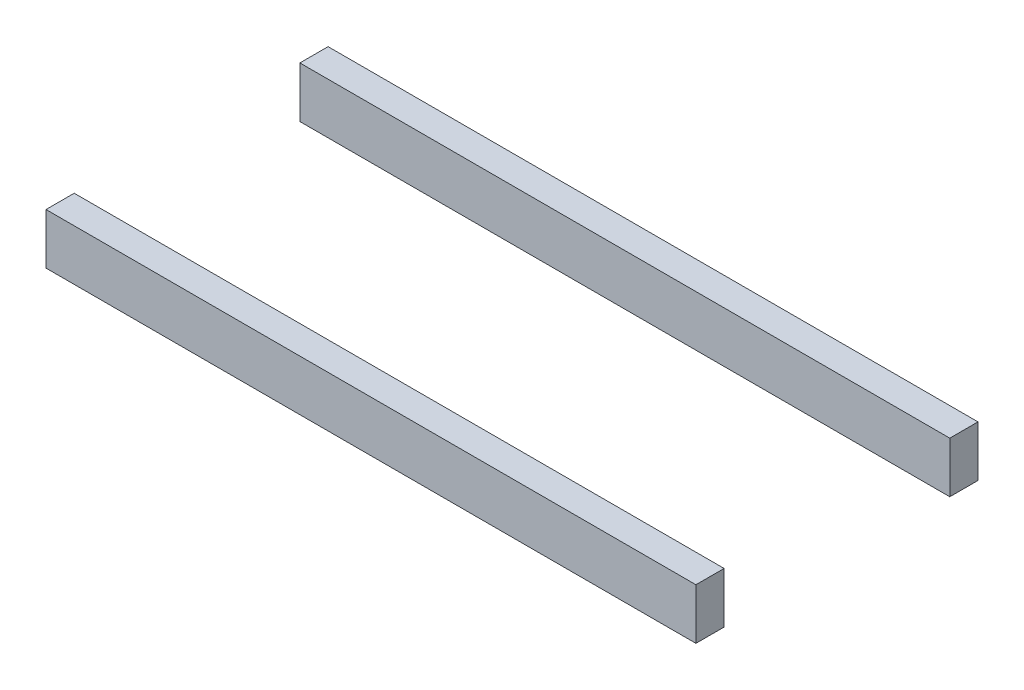
SolidWorks part; units mm, degrees
ref_plane "Front Plane" through (0, 0, 0) normal (0, 0, 1) x (1, 0, 0)
ref_plane "Top Plane" through (0, 0, 0) normal (0, 1, 0) x (1, 0, 0)
ref_plane "Right Plane" through (0, 0, 0) normal (1, 0, 0) x (0, 0, -1)
sketch "Sketch1" plane through (0, 0, 0) normal (0, 0, 1) x (1, 0, 0)
  line L1 (-27.598, -25) -> (27.598, -25)
  line L2 (-27.598, -25) -> (-27.598, 25)
  line L3 (-27.598, 25) -> (27.598, 25)
  line L4 (27.598, -25) -> (27.598, 25)
  line L5 (-27.598, -25) -> (27.598, 25) construction
  line L6 (-27.598, 25) -> (27.598, -25) construction
  point P0 (0, 0)
  dimension "D1" = 50
extrude "Boss-Extrude1" add sketch "Sketch1" against normal blind 70
sketch "Sketch2" plane through (0, 25, 0) normal (0, 1, 0) x (1, 0, 0)
  line L0 (27.598, 70) -> (27.598, 0) construction
  line L1 (-27.598, 0) -> (27.598, 0)
  line L2 (-27.598, 0) -> (-27.598, 15)
  line L3 (-27.598, 15) -> (27.598, 15)
  line L4 (27.598, 0) -> (27.598, 15)
  line L5 (-27.598, 70) -> (-27.598, 0) construction
  line L6 (27.598, 70) -> (-27.598, 70)
  line L7 (27.598, 70) -> (27.598, 55)
  line L8 (27.598, 55) -> (-27.598, 55)
  line L9 (-27.598, 70) -> (-27.598, 55)
  dimension "D1" = 15
  dimension "D2" = 15
extrude "Boss-Extrude2" add sketch "Sketch2" along normal blind 10
sketch "Sketch3" plane through (-27.598, 0, 0) normal (-1, 0, 0) x (0, 0, 1)
  line L0 (0, -25) -> (0, 35)
  line L1 (0, 35) -> (-15, 35)
  line L2 (-15, 35) -> (-15, 25)
  line L3 (-15, 25) -> (-55, 25)
  line L4 (-55, 25) -> (-55, 35)
  line L5 (-55, 35) -> (-70, 35)
  line L6 (-70, 35) -> (-70, -25)
  line L7 (-70, -25) -> (0, -25)
extrude "Boss-Extrude3" add sketch "Sketch3" along normal blind 60
sketch "Sketch4" plane through (-87.598, 0, 0) normal (-1, 0, 0) x (0, 0, 1)
  line L0 (-45, -25) -> (-25, -25)
  line L1 (-70, -25) -> (0, -25) construction
  line L2 (-45, -25) -> (-45, -15.25)
  line L3 (-45, -15.25) -> (-25, -15.25)
  line L4 (-25, -15.25) -> (-25, -25)
  line L6 (-70, -6.0529) -> (0, -6.0529) construction
  line L7 (-70, 35) -> (-70, -25) construction
  line L8 (0, -25) -> (0, 35) construction
  point P5 (-35, -25)
  point P13 (-35, -6.0529)
  dimension "D1" = 20
extrude "Boss-Extrude4" add sketch "Sketch4" along normal blind 25
sketch "Sketch5" plane through (0, -15.25, 0) normal (0, 1, 0) x (1, 0, 0)
  line L0 (-112.598, 45) -> (-87.598, 45) construction
  line L1 (-112.598, 25) -> (-102.598, 25)
  line L2 (-112.598, 25) -> (-112.598, 45)
  line L3 (-112.598, 45) -> (-102.598, 45)
  line L4 (-102.598, 25) -> (-102.598, 45)
extrude "Boss-Extrude5" add sketch "Sketch5" along normal blind 10
sketch "Sketch6" plane through (27.598, 0, 0) normal (1, 0, 0) x (0, 0, -1)
  line L0 (70, -25) -> (70, 35) construction
  line L1 (0, 35) -> (70, 35)
  line L2 (0, 35) -> (0, 34)
  line L3 (0, 34) -> (70, 34)
  line L4 (70, 35) -> (70, 34)
  dimension "D1" = 1
extrude "Cut-Extrude1" cut sketch "Sketch6" against normal through all
sketch "Sketch7" plane through (27.598, 0, 0) normal (1, 0, 0) x (0, 0, -1)
  line L0 (70, -25) -> (0, -25) construction
  line L1 (0, 34) -> (10, 34)
  line L2 (0, 34) -> (0, -25)
  line L3 (0, -25) -> (10, -25)
  line L4 (10, 34) -> (10, -25)
  line L6 (70, 34) -> (60, 34)
  line L7 (70, 34) -> (70, -25)
  line L8 (70, -25) -> (60, -25)
  line L9 (60, 34) -> (60, -25)
extrude "Cut-Extrude2" cut sketch "Sketch7" against normal through all
sketch "Sketch8" plane through (0, -25, 0) normal (0, -1, 0) x (1, 0, 0)
  line L1 (27.598, -60) -> (-118.4275, -60)
  line L2 (27.598, -60) -> (27.598, -6.2864)
  line L3 (27.598, -6.2864) -> (-118.4275, -6.2864)
  line L4 (-118.4275, -60) -> (-118.4275, -6.2864)
extrude "Cut-Extrude3" cut sketch "Sketch8" against normal blind 50
